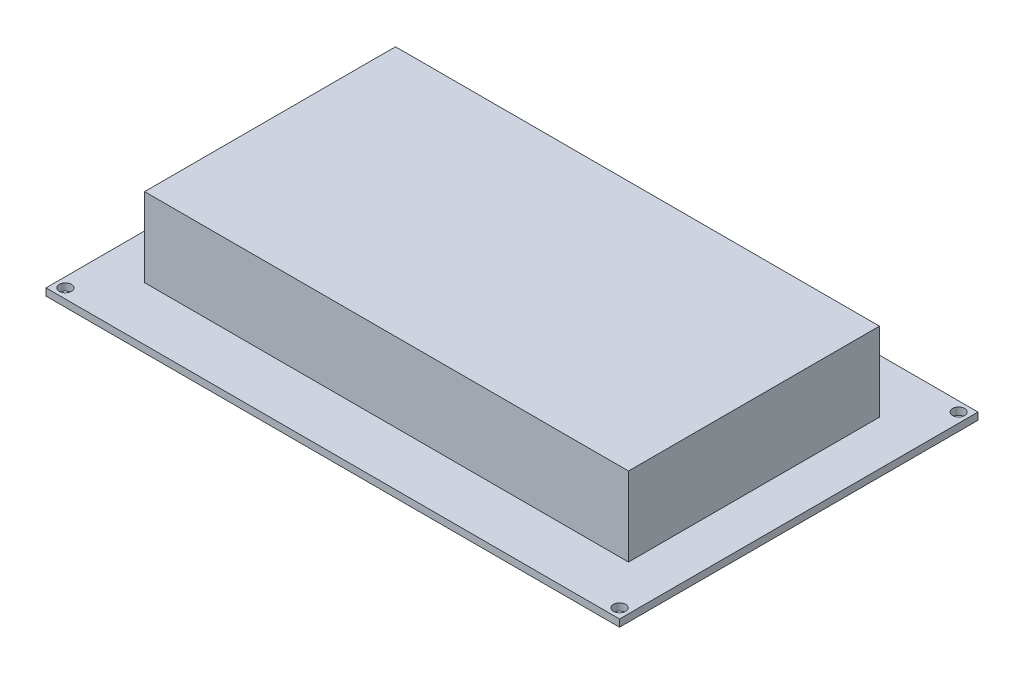
SolidWorks part; units mm, degrees
ref_plane "정면" through (0, 0, 0) normal (0, 0, 1) x (1, 0, 0)
ref_plane "윗면" through (0, 0, 0) normal (0, 1, 0) x (1, 0, 0)
ref_plane "우측면" through (0, 0, 0) normal (1, 0, 0) x (0, 0, -1)
sketch "스케치1" plane through (0, 0, 0) normal (0, 1, 0) x (1, 0, 0)
  line L1 (80, -50) -> (-80, -50)
  line L2 (80, -50) -> (80, 50)
  line L3 (80, 50) -> (-80, 50)
  line L4 (-80, -50) -> (-80, 50)
  line L5 (80, -50) -> (-80, 50) construction
  line L6 (80, 50) -> (-80, -50) construction
  point P0 (0, 0)
  dimension "D1" = 160
  dimension "D2" = 100
extrude "보스-돌출1" add sketch "스케치1" along normal blind 2
sketch "스케치2" plane through (0, 2, 0) normal (0, 1, 0) x (1, 0, 0)
  line L0 (80, 0) -> (0, 0) construction
  line L1 (80, -50) -> (80, 50) construction
  line L2 (0, 0) -> (0, 50) construction
  line L3 (80, 50) -> (-80, 50) construction
  line L4 (80, 47.3) -> (77.3, 47.3) construction
  line L5 (77.3, 47.3) -> (77.3, 50) construction
  circle A0 centre (77.3, 47.3) radius 1.7
  circle A1 centre (77.3, -47.3) radius 1.7
  circle A2 centre (-77.3, -47.3) radius 1.7
  circle A3 centre (-77.3, 47.3) radius 1.7
  dimension "D1" = 3.4
  dimension "D2" = 1
extrude "컷-돌출1" cut sketch "스케치2" against normal through all
sketch "스케치3" plane through (0, 2, 0) normal (0, 1, 0) x (1, 0, 0)
  line L1 (67.5, -35) -> (-67.5, -35)
  line L2 (67.5, -35) -> (67.5, 35)
  line L3 (67.5, 35) -> (-67.5, 35)
  line L4 (-67.5, -35) -> (-67.5, 35)
  line L5 (67.5, -35) -> (-67.5, 35) construction
  line L6 (67.5, 35) -> (-67.5, -35) construction
  point P0 (0, 0)
  dimension "D1" = 70
  dimension "D2" = 135
extrude "보스-돌출2" add sketch "스케치3" along normal blind 22
